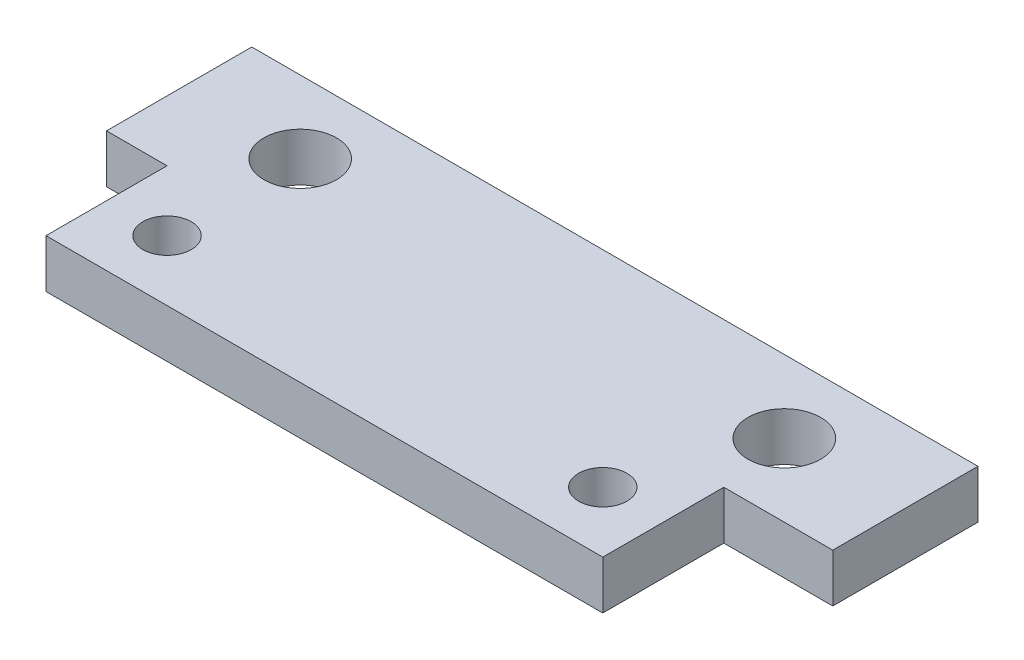
SolidWorks part; units mm, degrees
ref_plane "前视基准面" through (0, 0, 0) normal (0, 0, 1) x (1, 0, 0)
ref_plane "上视基准面" through (0, 0, 0) normal (0, 1, 0) x (1, 0, 0)
ref_plane "右视基准面" through (0, 0, 0) normal (1, 0, 0) x (0, 0, -1)
sketch "草图1" plane through (0, 0, 0) normal (0, 1, 0) x (1, 0, 0)
  line L0 (5, 3) -> (25, 3) construction
  line L1 (0, 0) -> (30, 0)
  line L2 (0, 0) -> (0, 6)
  line L3 (0, 6) -> (30, 6)
  line L4 (30, 0) -> (30, 6)
  circle A0 centre (5, 3) radius 1.5
  circle A1 centre (25, 3) radius 1.5
  dimension "D2" = 3
  dimension "D1" = 20
  dimension "D3" = 5
  dimension "D4" = 5
  dimension "D5" = 3
  dimension "D6" = 3
extrude "凸台-拉伸1" add sketch "草图1" along normal blind 2
sketch "草图2" plane through (0, 2, 0) normal (0, 1, 0) x (1, 0, 0)
  line L0 (2.5, 0) -> (2.5, -5)
  line L1 (0, 0) -> (30, 0) construction
  line L2 (2.5, -5) -> (25.5, -5)
  line L3 (25.5, -5) -> (25.5, 0)
  line L4 (25.5, 0) -> (2.5, 0)
  line L5 (5, -2.5) -> (23, -2.5) construction
  line L6 (15, 6) -> (15, 0) construction
  line L7 (30, 6) -> (0, 6) construction
  circle A0 centre (5, -2.5) radius 1
  circle A1 centre (23, -2.5) radius 1
  point P13 (14, 0)
  dimension "D4" = 2
  dimension "D1" = 18
  dimension "D2" = 2.5
  dimension "D3" = 2.5
  dimension "D5" = 2.5
  dimension "D6" = 2.5
  dimension "D7" = 1
extrude "凸台-拉伸2" add sketch "草图2" against normal up to surface (2 mm away) up to face at (5, 0, -1.5)
